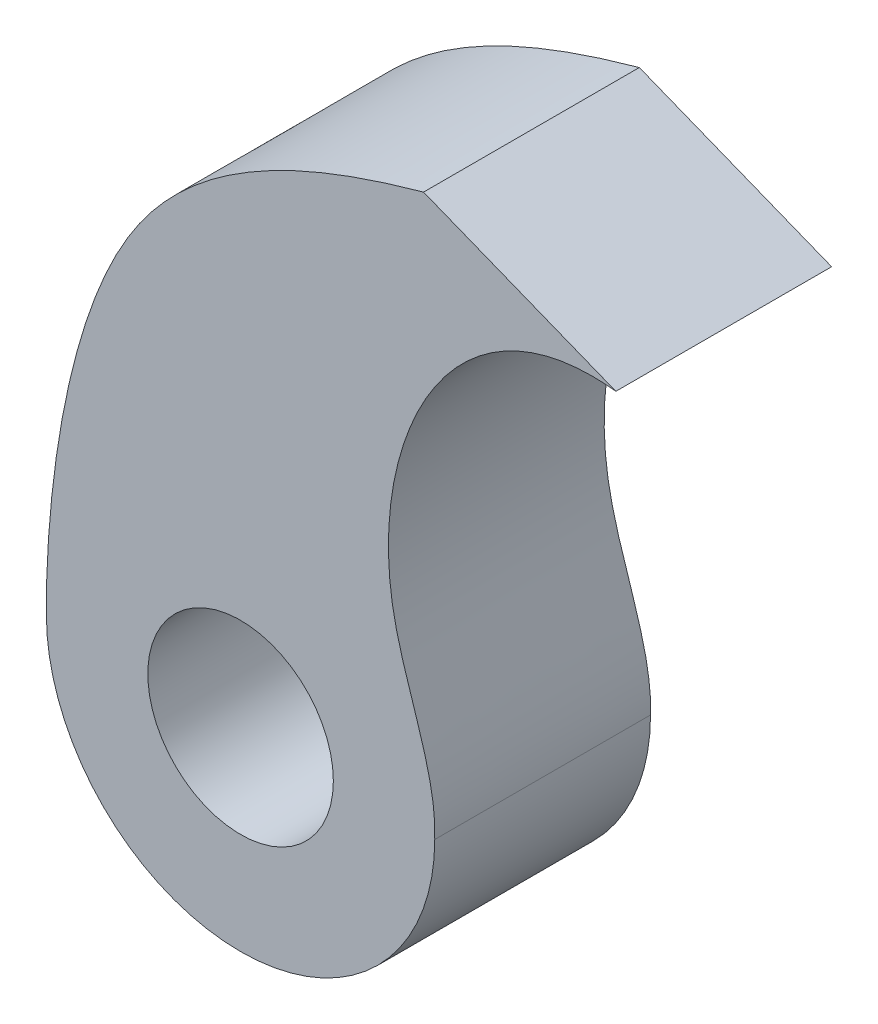
SolidWorks part; units mm, degrees
ref_plane "Front Plane" through (0, 0, 0) normal (0, 0, 1) x (1, 0, 0)
ref_plane "Top Plane" through (0, 0, 0) normal (0, 1, 0) x (1, 0, 0)
ref_plane "Right Plane" through (0, 0, 0) normal (1, 0, 0) x (0, 0, -1)
sketch "Sketch1" plane through (0, 0, 0) normal (0, 0, 1) x (1, 0, 0)
  line L0 (-8.7863, 52.647) -> (-17.6976, 56.1882)
  circle A0 centre (-26.1796, 30.4605) radius 4.3
  arc A1 (-35.1796, 30.4605) -> (-17.1796, 30.4605) centre (-26.1796, 30.4605) ccw
  spline S0 degree 3 poles (-17.1796, 30.4605) (-17.0733, 33.2175) (-22.0367, 41.8303) (-16.3931, 53.5088) (-8.7863, 52.647) knots 0 0 0 0 0.305227 1 1 1 1
  spline S1 degree 3 poles (-35.1796, 30.4605) (-35.2235, 33.9177) (-34.2012, 49.7812) (-23.153, 54.6719) (-17.6976, 56.1882) knots 0 0 0 0 0.555506 1 1 1 1
  point P10 (-30.9938, 48.1561)
  dimension "D1" = 8.6
  dimension "D2" = 18
extrude "Boss-Extrude1" add sketch "Sketch1" along normal blind 10
